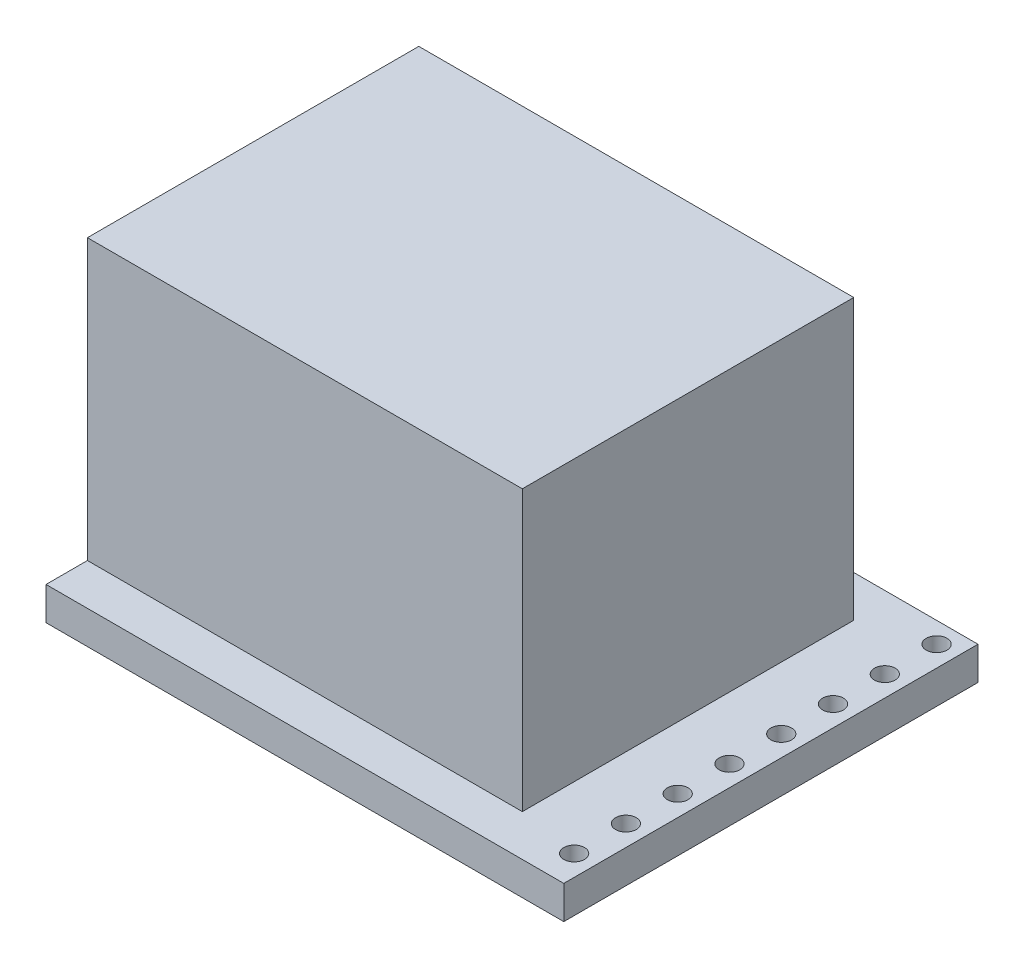
SolidWorks part; units mm, degrees
ref_plane "Front Plane" through (0, 0, 0) normal (0, 0, 1) x (1, 0, 0)
ref_plane "Top Plane" through (0, 0, 0) normal (0, 1, 0) x (1, 0, 0)
ref_plane "Right Plane" through (0, 0, 0) normal (1, 0, 0) x (0, 0, -1)
sketch "Sketch1" plane through (0, 0, 0) normal (0, 1, 0) x (1, 0, 0)
  line L1 (-12.5, -10) -> (12.5, -10)
  line L2 (-12.5, -10) -> (-12.5, 10)
  line L3 (-12.5, 10) -> (12.5, 10)
  line L4 (12.5, -10) -> (12.5, 10)
  line L5 (-12.5, -10) -> (12.5, 10) construction
  line L6 (-12.5, 10) -> (12.5, -10) construction
  point P0 (0, 0)
  dimension "D1" = 20
  dimension "D2" = 25
extrude "Boss-Extrude1" add sketch "Sketch1" against normal blind 1.6
sketch "Sketch2" plane through (0, 0, 0) normal (0, 1, 0) x (1, 0, 0)
  line L0 (-12.5, 10) -> (-12.5, -10) construction
  line L1 (-12.5, 8) -> (8.5, 8)
  line L2 (-12.5, 8) -> (-12.5, -8)
  line L3 (-12.5, -8) -> (8.5, -8)
  line L4 (8.5, 8) -> (8.5, -8)
  point P6 (-12.5, 0)
  point P7 (8.5, 0)
  dimension "D1" = 21
  dimension "D2" = 16
extrude "Boss-Extrude2" add sketch "Sketch2" along normal blind 13.5
sketch "Sketch3" plane through (-12.5, 0, 0) normal (-1, 0, 0) x (0, 0, 1)
  line L0 (-8, 13.5) -> (8, 13.5) construction
  line L1 (-6.2, 3.75) -> (-3.5, 3.75)
  line L2 (-6.2, 3.75) -> (-6.2, 10.75)
  line L3 (-6.2, 10.75) -> (6.2, 10.75)
  line L4 (6.2, 3.75) -> (6.2, 10.75)
  line L5 (-6.2, 3.75) -> (6.2, 10.75) construction
  line L6 (-6.2, 10.75) -> (6.2, 3.75) construction
  line L7 (8, 13.5) -> (8, 0) construction
  line L8 (-8, 13.5) -> (-8, 0) construction
  line L9 (3.5, 3.75) -> (6.2, 3.75)
  line L11 (3.5, 3.75) -> (3.5, 2.25)
  line L12 (3.5, 2.25) -> (-3.5, 2.25)
  line L13 (-3.5, 3.75) -> (-3.5, 2.25)
  point P0 (0, 7.25)
  dimension "D1" = 2.75
  dimension "D2" = 1.8
  dimension "D3" = 1.8
  dimension "D4" = 7
  dimension "D5" = 1.5
  dimension "D6" = 7
  dimension "D7" = 2.7
extrude "Cut-Extrude1" cut sketch "Sketch3" against normal blind 13.5
sketch "Sketch4" plane through (0, 0, 0) normal (0, 1, 0) x (1, 0, 0)
  line L0 (12.5, 10) -> (-12.5, 10) construction
  line L1 (12.5, -10) -> (12.5, 10) construction
  line L2 (11.5, 9) -> (11.5, 6.5) construction
  circle A0 centre (11.5, 9) radius 0.5
  circle A1 centre (11.5, 6.5) radius 0.5
  circle A2 centre (11.5, 4) radius 0.5
  circle A3 centre (11.5, 1.5) radius 0.5
  circle A4 centre (11.5, -1) radius 0.5
  circle A5 centre (11.5, -3.5) radius 0.5
  circle A6 centre (11.5, -6) radius 0.5
  circle A7 centre (11.5, -8.5) radius 0.5
  dimension "D2" = 1
  dimension "D1" = 1
  dimension "D3" = 1
  dimension "D5" = 2.5
  dimension "D4" = 8
extrude "Cut-Extrude2" cut sketch "Sketch4" against normal blind 13.5
sketch "Sketch5" plane through (0, -1.6, 0) normal (0, -1, 0) x (-1, 0, 0)
  line L0 (-6.5, -4) -> (-6.5, 4) construction
  line L1 (-8.5, -4) -> (-8.5, 4)
  line L2 (-4.5, -4) -> (-4.5, 4)
  line L3 (-12.5, -10) -> (-12.5, 10) construction
  arc A0 (-8.5, -4) -> (-4.5, -4) centre (-6.5, -4) ccw
  arc A1 (-4.5, 4) -> (-8.5, 4) centre (-6.5, 4) ccw
  point P2 (-6.5, 0)
  point P9 (-12.5, 0)
  dimension "D3" = 8
  dimension "D1" = 6
  dimension "D2" = 4
extrude "Boss-Extrude3" add sketch "Sketch5" along normal blind 2
sketch "Sketch6" plane through (0, -1.6, 0) normal (0, -1, 0) x (1, 0, 0)
  line L0 (-12.5, 10) -> (12.5, 10) construction
  line L1 (12.5, -10) -> (-12.5, -10) construction
  line L2 (-12.5, -10) -> (-12.5, 10) construction
  circle A0 centre (-2.5, 6) radius 1.5
  circle A1 centre (-2.5, -6) radius 1.5
  dimension "D1" = 3
  dimension "D2" = 3
  dimension "D3" = 4
  dimension "D4" = 4
  dimension "D5" = 10
extrude "Boss-Extrude4" add sketch "Sketch6" along normal blind 2
